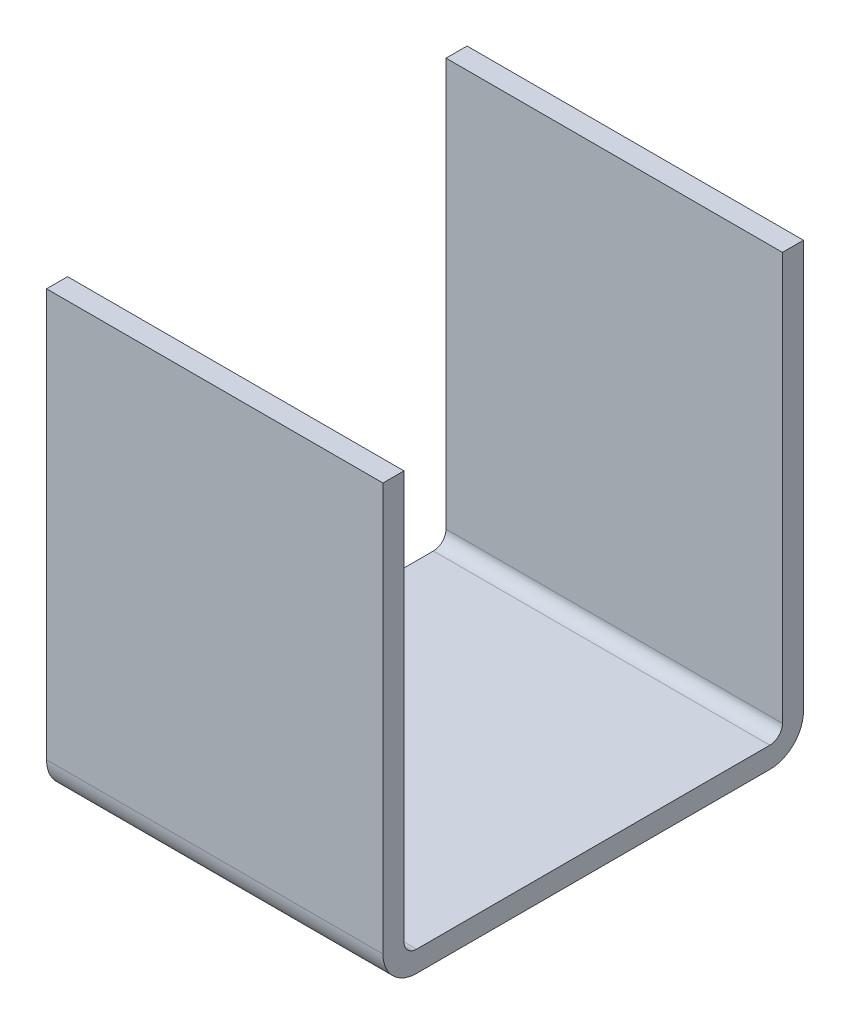
SolidWorks part; units mm, degrees
ref_plane "Front Plane" through (0, 0, 0) normal (0, 0, 1) x (1, 0, 0)
ref_plane "Top Plane" through (0, 0, 0) normal (0, 1, 0) x (1, 0, 0)
ref_plane "Right Plane" through (0, 0, 0) normal (1, 0, 0) x (0, 0, -1)
sketch "Sketch1" plane through (0, 0, 0) normal (0, 1, 0) x (1, 0, 0)
  line L1 (0, 0) -> (40, 0)
  line L2 (0, 0) -> (0, 50)
  line L3 (0, 50) -> (40, 50)
  line L4 (40, 0) -> (40, 50)
  dimension "D1" = 40
  dimension "D2" = 50
extrude "Boss-Extrude1" add sketch "Sketch1" along normal blind 2.5
sketch "Sketch2" plane through (0, 2.5, 0) normal (0, 1, 0) x (1, 0, 0)
  line L0 (40, 0) -> (40, 50) construction
  line L1 (0, 50) -> (40, 50)
  line L2 (0, 50) -> (0, 47.5)
  line L3 (0, 47.5) -> (40, 47.5)
  line L4 (40, 50) -> (40, 47.5)
  line L5 (0, 50) -> (0, 0) construction
  line L6 (40, 0) -> (0, 0)
  line L7 (40, 0) -> (40, 2.5)
  line L8 (40, 2.5) -> (0, 2.5)
  line L9 (0, 0) -> (0, 2.5)
  dimension "D1" = 2.5
extrude "Boss-Extrude2" add sketch "Sketch2" along normal blind 50
fillet "Fillet1" radius 4 2 edges at (20, 0, 0) (20, 0, -50)
fillet "Fillet2" radius 1.5 2 edges at (20, 2.5, -2.5) (20, 2.5, -47.5)
